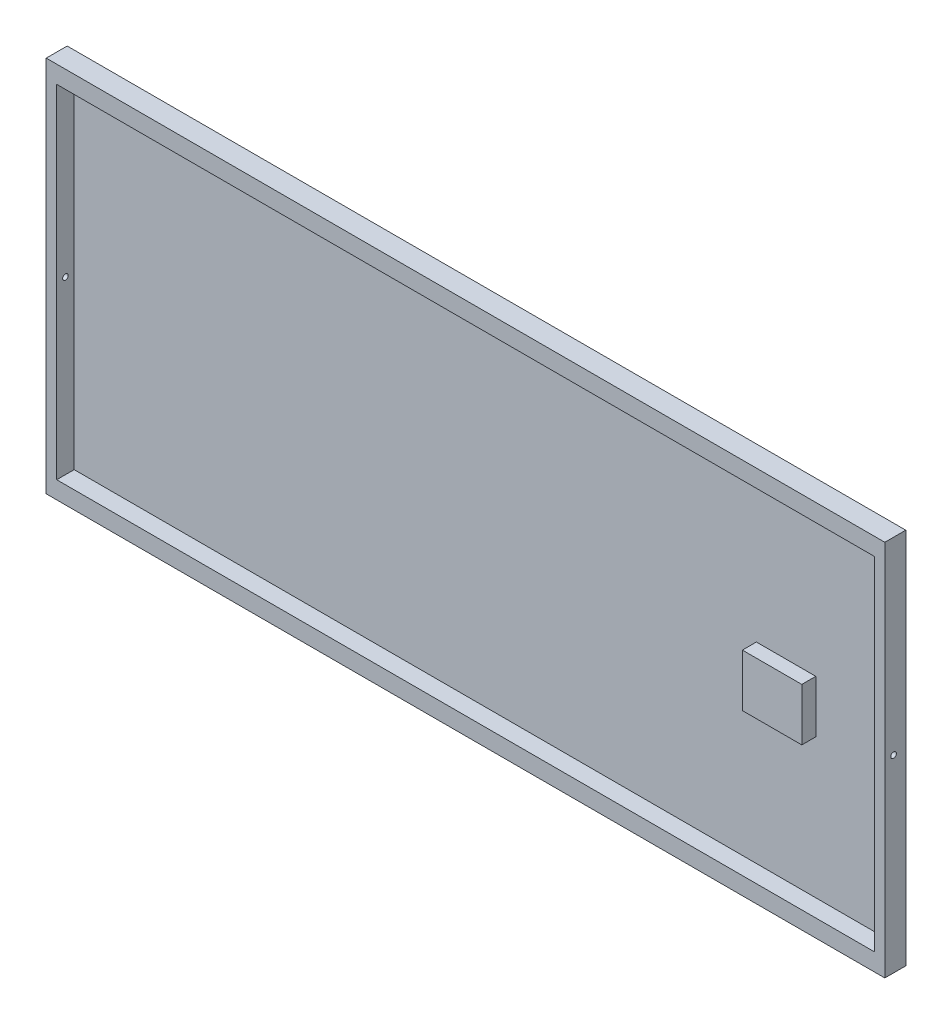
SolidWorks part; units mm, degrees
ref_plane "前视基准面" through (0, 0, 0) normal (0, 0, 1) x (1, 0, 0)
ref_plane "上视基准面" through (0, 0, 0) normal (0, 1, 0) x (1, 0, 0)
ref_plane "右视基准面" through (0, 0, 0) normal (1, 0, 0) x (0, 0, -1)
sketch "草图1" plane through (0, 0, 0) normal (0, 0, 1) x (1, 0, 0)
  line L1 (-60.5395, 25.2248) -> (1139.4605, 25.2248)
  line L2 (-60.5395, 25.2248) -> (-60.5395, -514.7752)
  line L3 (-60.5395, -514.7752) -> (1139.4605, -514.7752)
  line L4 (1139.4605, 25.2248) -> (1139.4605, -514.7752)
  dimension "D1" = 1200
  dimension "D2" = 540
extrude "凸台-拉伸1" add sketch "草图1" along normal blind 30
sketch "草图2" plane through (0, 0, 30) normal (0, 0, 1) x (1, 0, 0)
  line L0 (-60.5395, 25.2248) -> (-60.5395, -514.7752) construction
  line L1 (-45.5395, 0.2248) -> (1124.4605, 0.2248)
  line L2 (-45.5395, 0.2248) -> (-45.5395, -489.7752)
  line L3 (-45.5395, -489.7752) -> (1124.4605, -489.7752)
  line L4 (1124.4605, 0.2248) -> (1124.4605, -489.7752)
  line L5 (1139.4605, -514.7752) -> (1139.4605, 25.2248) construction
  line L6 (-60.5395, -514.7752) -> (1139.4605, -514.7752) construction
  line L7 (1139.4605, 25.2248) -> (-60.5395, 25.2248) construction
  dimension "D1" = 15
  dimension "D2" = 15
  dimension "D3" = 25
  dimension "D4" = 25
extrude "切除-拉伸1" cut sketch "草图2" against normal blind 25
sketch "草图3" plane through (-60.5395, 0, 0) normal (-1, 0, 0) x (0, 0, 1)
  circle A0 centre (17.5, -244.7752) radius 4
  dimension "D2" = 8
extrude "切除-拉伸2" cut sketch "草图3" against normal blind 12000
sketch "草图4" plane through (0, 0, 5) normal (0, 0, 1) x (1, 0, 0)
  line L1 (930.6729, -215.3003) -> (1015.6729, -215.3003)
  line L2 (930.6729, -215.3003) -> (930.6729, -290.3003)
  line L3 (930.6729, -290.3003) -> (1015.6729, -290.3003)
  line L4 (1015.6729, -215.3003) -> (1015.6729, -290.3003)
  dimension "D1" = 85
  dimension "D2" = 75
extrude "凸台-拉伸2" add sketch "草图4" along normal blind 20
sketch "草图5" plane through (930.6729, 0, 0) normal (-1, 0, 0) x (0, 0, 1)
  circle A0 centre (15.687, -230.169) radius 2.5
  circle A2 centre (15.687, -239.792) radius 2.5
  dimension "D1" = 5
  dimension "D3" = 5
extrude "凸台-拉伸3" add sketch "草图5" along normal blind 5
